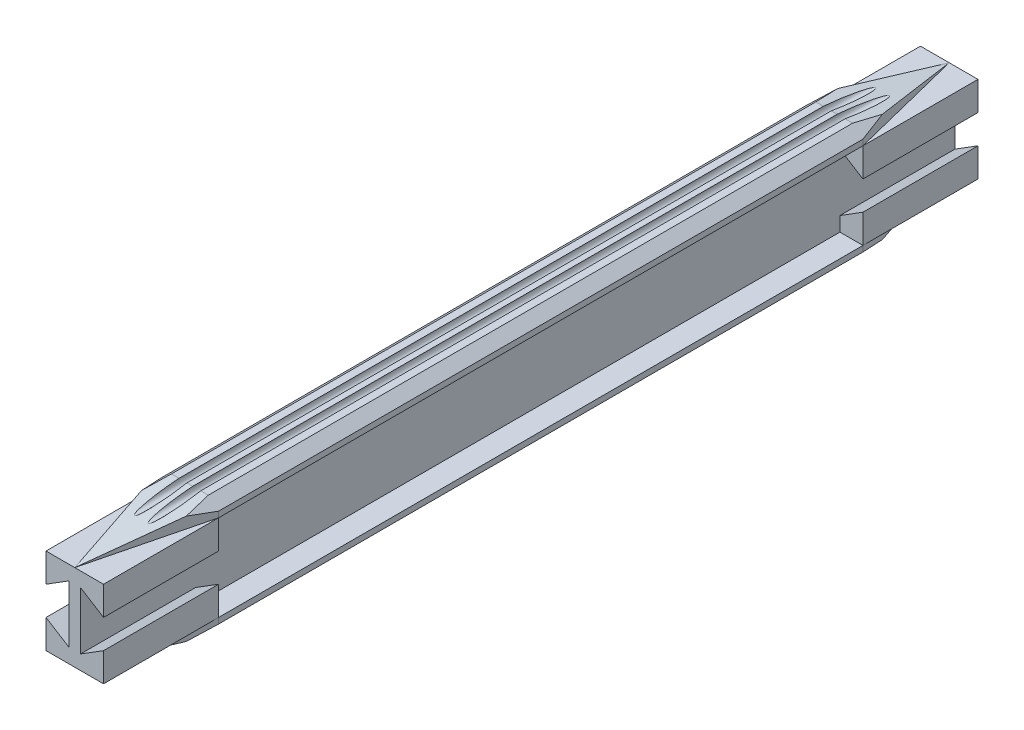
SolidWorks part; units mm, degrees
ref_plane "Front Plane" through (0, 0, 0) normal (0, 0, 1) x (1, 0, 0)
ref_plane "Top Plane" through (0, 0, 0) normal (0, 1, 0) x (1, 0, 0)
ref_plane "Right Plane" through (0, 0, 0) normal (1, 0, 0) x (0, 0, -1)
sketch "Sketch1" plane through (0, 0, 0) normal (1, 0, 0) x (0, 0, -1)
  line L1 (-76, -7.5) -> (76, -7.5)
  line L2 (-76, -7.5) -> (-76, 7.5)
  line L3 (-76, 7.5) -> (76, 7.5)
  line L4 (76, -7.5) -> (76, 7.5)
  line L5 (-76, -7.5) -> (76, 7.5) construction
  line L6 (-76, 7.5) -> (76, -7.5) construction
  point P1 (0, 0)
  dimension "D1" = 152
  dimension "D2" = 15
extrude "Boss-Extrude1" add sketch "Sketch1" along normal mid plane 2
sketch "Sketch2" plane through (1, 0, 0) normal (1, 0, 0) x (0, 0, -1)
  line L0 (-76, -7.5) -> (76, -7.5) construction
  line L1 (76, 7.5) -> (56, 7.5)
  line L2 (76, 7.5) -> (76, -7.5)
  line L3 (76, -7.5) -> (56, -7.5)
  line L4 (56, 7.5) -> (56, -7.5)
  dimension "D1" = 20
extrude "Boss-Extrude2" add sketch "Sketch2" along normal blind 4
sketch "Sketch3" plane through (0, 0, -56) normal (0, 0, 1) x (1, 0, 0)
  line L0 (5, 0) -> (1, 0) construction
  line L1 (5, 7.5) -> (5, -7.5) construction
  line L2 (1, 7.5) -> (1, -7.5) construction
  line L3 (5, 2.5) -> (1, 5)
  line L4 (1, 5) -> (1, -5)
  line L5 (1, -5) -> (5, -2.5)
  line L6 (5, -2.5) -> (5, 2.5)
  dimension "D1" = 5
  dimension "D2" = 10
  dimension "D3" = 4
extrude "Cut-Extrude1" cut sketch "Sketch3" against normal through all
mirror "Mirror1" about plane through (0, 0, 0) normal (1, 0, 0) of "Cut-Extrude1", "Boss-Extrude2"
mirror "Mirror2" about plane through (0, 0, 0) normal (0, 0, 1) of "Mirror1", "Boss-Extrude2", "Cut-Extrude1"
sketch "Sketch7" plane through (0, 7.5, 0) normal (0, 1, 0) x (1, 0, 0)
  line L0 (0, -58.25) -> (0, 49941.75) construction
  line L1 (5, -76) -> (-5, -76) construction
  line L2 (0, -76) -> (-5, -56)
  line L3 (-5, -56) -> (-1, -56) construction
  line L4 (-5, -56) -> (-5, 56)
  line L5 (-5, 56) -> (-1, 56) construction
  line L6 (-5, 56) -> (0, 76)
  line L7 (5, 76) -> (-5, 76) construction
  line L8 (5, 56) -> (0, 76)
  line L9 (5, -56) -> (5, 56)
  line L10 (0, -76) -> (5, -56)
  line L11 (1, 56) -> (1, -56) construction
  point P4 (0, -76)
  dimension "D1" = 4
extrude "Boss-Extrude5" add sketch "Sketch7" along normal blind 2.5
sketch "Sketch8" plane through (-5, 0, 0) normal (-1, 0, 0) x (0, 0, 1)
  line L0 (-56, 10) -> (-76, 7.5)
  line L1 (-76, 7.5) -> (-76, 10)
  line L2 (-76, 10) -> (-56, 10)
  line L3 (0, 9) -> (0, -49991) construction
  line L4 (-56, 10) -> (56, 10) construction
  line L5 (76, 10) -> (56, 10)
  line L6 (76, 7.5) -> (76, 10)
  line L7 (56, 10) -> (76, 7.5)
  point P17 (0, 10)
extrude "Cut-Extrude2" cut sketch "Sketch8" against normal through all
sketch "Sketch9" plane through (0, 0, 76) normal (0, 0, 1) x (1, 0, 0)
  line L0 (0, 7.5) -> (0, -49992.5) construction
  line L1 (5, 7.5) -> (0, 7.5) construction
  circle A0 centre (1.2, 9.7) radius 0.75
  circle A1 centre (-1.2, 9.7) radius 0.75
  dimension "D2" = 1.5
  dimension "D1" = 1.2
  dimension "D3" = 2.2
extrude "Cut-Extrude3" cut sketch "Sketch9" against normal through all
mirror "Mirror4" about plane through (0, 0, 0) normal (0, 1, 0) of "Boss-Extrude5", "Cut-Extrude2", "Cut-Extrude3"
sketch "Sketch10" plane through (0, 0, -76) normal (0, 0, -1) x (-1, 0, 0)
  line L0 (-5, 8.5) -> (-3.2, 10)
  line L1 (-5, 10) -> (-5, 7.5) construction
  line L2 (-5, 10) -> (-1.8874, 10) construction
  line L3 (-3.2, 10) -> (-5, 10)
  line L4 (-5, 10) -> (-5, 8.5)
  line L5 (-5, 7.5) -> (0, 7.5) construction
  line L6 (0, 9) -> (0, -49991) construction
  line L7 (-0.5126, 10) -> (0.5126, 10) construction
  line L8 (0, 0) -> (50000, 0) construction
  line L9 (5, 10) -> (5, 8.5)
  line L10 (3.2, 10) -> (5, 10)
  line L11 (5, 8.5) -> (3.2, 10)
  line L12 (-5, -10) -> (-5, -8.5)
  line L13 (-3.2, -10) -> (-5, -10)
  line L14 (-5, -8.5) -> (-3.2, -10)
  line L15 (5, -8.5) -> (3.2, -10)
  line L16 (3.2, -10) -> (5, -10)
  line L17 (5, -10) -> (5, -8.5)
  arc A0 (-1.8874, 10) -> (-0.5126, 10) centre (-1.2, 9.7) ccw construction
  point P17 (0, 10)
  dimension "D1" = 1
  dimension "D2" = 2
extrude "Cut-Extrude4" cut sketch "Sketch10" against normal through all
